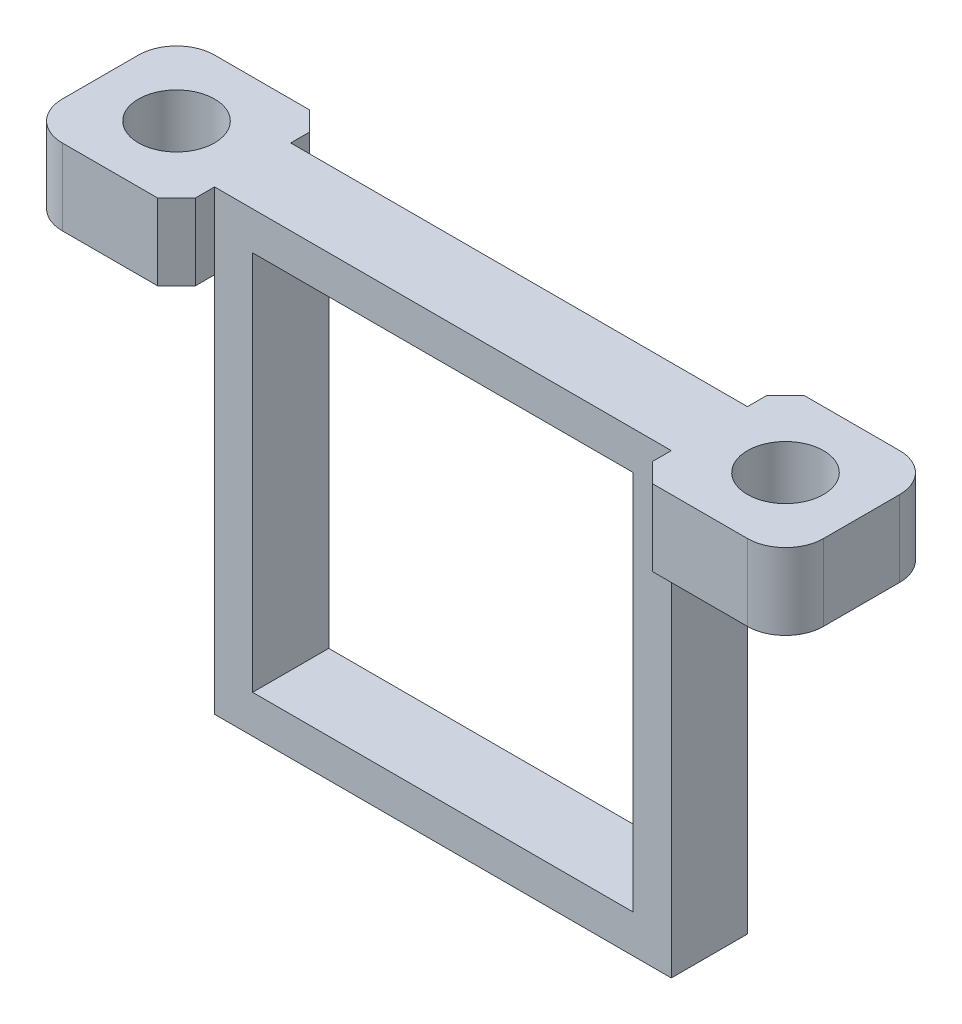
SolidWorks part; units mm, degrees
ref_plane "Спереди" through (0, 0, 0) normal (0, 0, 1) x (1, 0, 0)
ref_plane "Сверху" through (0, 0, 0) normal (0, 1, 0) x (1, 0, 0)
ref_plane "Справа" through (0, 0, 0) normal (1, 0, 0) x (0, 0, -1)
other "Configuration Table"
sketch "Эскиз1" plane through (0, 0, 0) normal (0, 0, 1) x (1, 0, 0)
  line L0 (0, 10) -> (10, 10)
  line L1 (-10, -10) -> (10, -10)
  line L2 (-10, -10) -> (-10, 10)
  line L3 (-10, 10) -> (10, 10)
  line L4 (10, -10) -> (10, 10)
  line L5 (0, 10) -> (-10, 10)
  line L8 (0, 10) -> (-10, 10)
  line L9 (0, 10) -> (10, 10)
  line L19 (-10, 0) -> (10, 0) construction
  line L29 (0, 10) -> (0, -10) construction
  line L48 (-12, -12) -> (12, -12)
  line L49 (12, -12) -> (12, 12)
  line L50 (-12, -12) -> (-12, 12)
  line L51 (-12, 12) -> (12, 12)
  point P5 (0, 0)
  point P8 (0, 0)
  point P9 (0, 0)
  point P10 (0, 0)
  point P13 (0, 0)
  point P14 (0, 0)
  point P17 (0, 0)
  point P34 (0, 0)
  point P52 (0, 0)
  point P57 (0, 0)
  dimension "D1" = 20
  dimension "D12" = 20
  dimension "D27" = 2
  dimension "D28" = 24
  dimension "D29" = 24
  dimension "D30" = 24
  dimension "D31" = 2
extrude "Бобышка-Вытянуть1" add sketch "Эскиз1" along normal blind 4
sketch "Эскиз6" plane through (0, 12, 0) normal (0, 1, 0) x (1, 0, 0)
  line L1 (-12, 2) -> (-18, 2)
  line L2 (-12, 2) -> (-12, -6)
  line L3 (-12, -6) -> (-18, -6)
  line L4 (-20, 0) -> (-20, -4)
  line L9 (-12, -2) -> (-38.0803, -2) construction
  line L10 (-12, -4) -> (-12, 0) construction
  arc A0 (-18, 2) -> (-20, 0) centre (-18, 0) ccw
  arc A1 (-20, -4) -> (-18, -6) centre (-18, -4) ccw
  circle A2 centre (-16, -2) radius 2
  point P8 (-12, -2)
  point P11 (-20, 2)
  point P14 (-20, -6)
  dimension "D3" = 2
  dimension "D4" = 2
  dimension "D5" = 4
  dimension "D1" = 8
  dimension "D2" = 8
  dimension "D6" = 4
extrude "Бобышка-Вытянуть2" add sketch "Эскиз6" against normal blind 4
chamfer "Фаска1" distance 1 angle 45 2 edges at (-12, 10, -2) (-12, 10, 6)
mirror "Зеркальное отражение1" about plane through (0, 0, 0) normal (1, 0, 0) of "Фаска1", "Бобышка-Вытянуть2"
